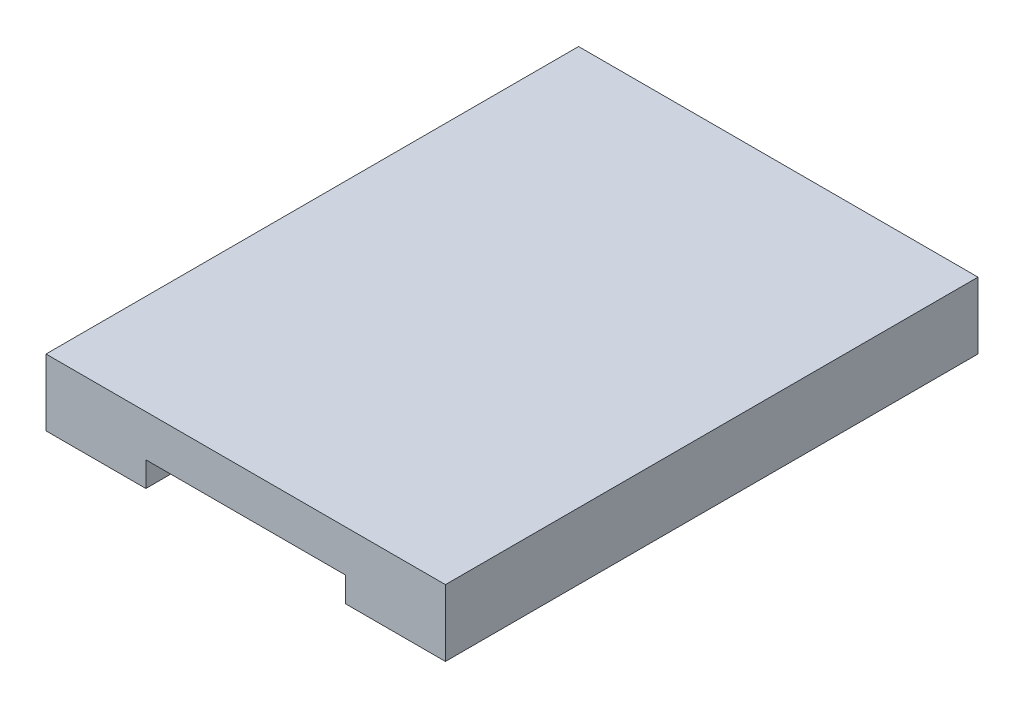
SolidWorks part; units mm, degrees
ref_plane "Front Plane" through (0, 0, 0) normal (0, 0, 1) x (1, 0, 0)
ref_plane "Top Plane" through (0, 0, 0) normal (0, 1, 0) x (1, 0, 0)
ref_plane "Right Plane" through (0, 0, 0) normal (1, 0, 0) x (0, 0, -1)
sketch "Sketch1" plane through (0, 0, 0) normal (0, 1, 0) x (1, 0, 0)
  line L1 (-38.1, 50.8) -> (38.1, 50.8)
  line L2 (-38.1, 50.8) -> (-38.1, -50.8)
  line L3 (-38.1, -50.8) -> (38.1, -50.8)
  line L4 (38.1, 50.8) -> (38.1, -50.8)
  line L5 (-38.1, 50.8) -> (38.1, -50.8) construction
  line L6 (-38.1, -50.8) -> (38.1, 50.8) construction
  point P0 (0, 0)
  dimension "D1" = 76.2
  dimension "D2" = 101.6
extrude "Boss-Extrude1" add sketch "Sketch1" along normal blind 12.7
sketch "Sketch2" plane through (0, 0, 0) normal (0, -1, 0) x (1, 0, 0)
  line L0 (-38.1, 50.8) -> (-19.05, 50.8) construction
  line L1 (-38.1, 50.8) -> (38.1, 50.8) construction
  line L3 (-19.05, 50.8) -> (19.05, 50.8)
  line L4 (-19.05, 50.8) -> (-19.05, 30.1498)
  line L5 (-19.05, 30.1498) -> (19.05, 30.1498)
  line L6 (19.05, 50.8) -> (19.05, 30.1498)
  dimension "D1" = 19.05
  dimension "D2" = 38.1
  dimension "D3" = 20.6502
extrude "Cut-Extrude1" cut sketch "Sketch2" against normal blind 4.7498
sketch "Sketch3" plane through (0, 0, -50.8) normal (0, 0, -1) x (-1, 0, 0)
  line L0 (-38.1, 12.7) -> (38.1, 0) construction
  circle A0 centre (0, 6.35) radius 3.81
  dimension "D1" = 7.62
extrude "Cut-Extrude2" cut sketch "Sketch3" against normal blind 6.35
